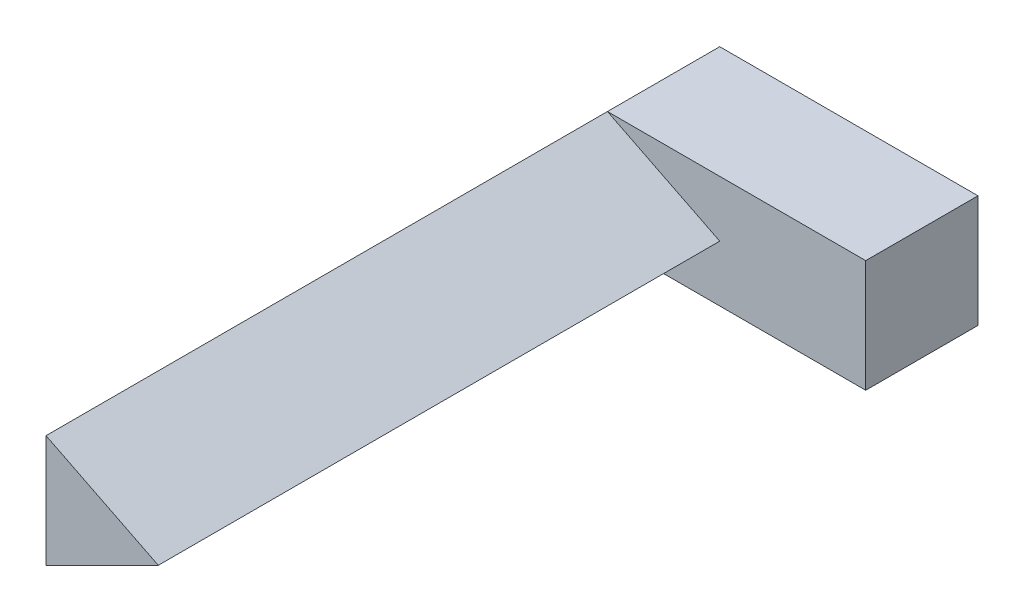
SolidWorks part; units mm, degrees
ref_plane "Front Plane" through (0, 0, 0) normal (0, 0, 1) x (1, 0, 0)
ref_plane "Top Plane" through (0, 0, 0) normal (0, 1, 0) x (1, 0, 0)
ref_plane "Right Plane" through (0, 0, 0) normal (1, 0, 0) x (0, 0, -1)
sketch "Sketch1" plane through (0, 0, 0) normal (0, 1, 0) x (1, 0, 0)
  line L0 (0, 0) -> (-23, 0)
  line L1 (0, 0) -> (0, -10)
  line L2 (0, -10) -> (-13, -10)
  line L3 (-13, -10) -> (-13, -60)
  line L4 (-23, 0) -> (-23, -60)
  line L5 (-23, -60) -> (-13, -60)
  dimension "D1" = 13
  dimension "D2" = 10
  dimension "D3" = 23
  dimension "D4" = 50
extrude "Boss-Extrude1" add sketch "Sketch1" along normal mid plane 10
sketch "Sketch2" plane through (0, 0, 60) normal (0, 0, 1) x (1, 0, 0)
  line L0 (-23, 5) -> (-13, 0)
  line L1 (-13, 5) -> (-13, -5) construction
  line L2 (-13, 0) -> (-23, -5)
  line L3 (-23, -5) -> (-13, -5)
  line L4 (-13, -5) -> (-13, 0)
  line L5 (-13, 5) -> (-23, 5)
  line L6 (-13, 5) -> (-13, 0)
  line M1 (-23, -5) -> (-13, -5)
  line M2 (-13, -5) -> (-13, 5)
  line M3 (-13, 5) -> (-23, 5)
extrude "Cut-Extrude1" cut sketch "Sketch2" against normal up to surface (50 mm away) contours L0 M3 M2 | L2 M2 M1 up to face at (-6.5, 0, 10)
